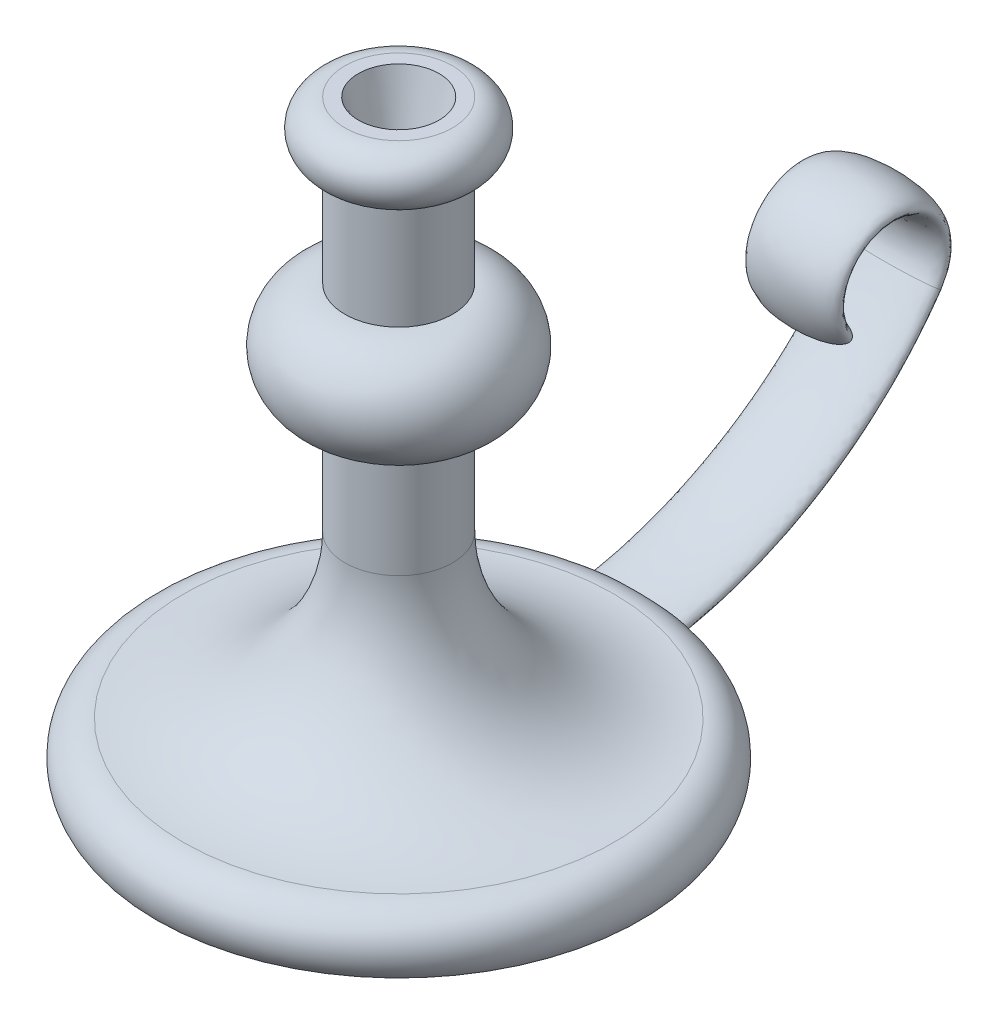
SolidWorks part; units mm, degrees
ref_plane "Спереди" through (0, 0, 0) normal (0, 0, 1) x (1, 0, 0)
ref_plane "Сверху" through (0, 0, 0) normal (0, 1, 0) x (1, 0, 0)
ref_plane "Справа" through (0, 0, 0) normal (1, 0, 0) x (0, 0, -1)
sketch "Эскиз1" plane through (0, 0, 0) normal (0, 0, 1) x (1, 0, 0)
  line L0 (90, 0) -> (0, 0)
  line L1 (0, 0) -> (0, 220)
  line L2 (0, 220) -> (20, 220)
  line L3 (20, 200) -> (20, 160)
  line L4 (20, 120) -> (20, 80)
  arc A0 (20, 220) -> (20, 200) centre (20, 210) cw
  arc A1 (20, 160) -> (20, 120) centre (20, 140) cw
  arc A2 (20, 80) -> (80, 20) centre (80, 80) ccw
  arc A3 (80, 20) -> (90, 0) centre (80, 7.5) cw
  point P14 (0, 0)
  point P15 (0, 0)
  dimension "D4" = 10
  dimension "D5" = 20
  dimension "D7" = 60
  dimension "D8" = 12.5
  dimension "D1" = 20
  dimension "D2" = 220
  dimension "D3" = 90
  dimension "D6" = 40
  dimension "D9" = 80
revolve "Повернуть1" add sketch "Эскиз1" angle 360 about L1
sketch "Эскиз2" plane through (0, 0, 0) normal (1, 0, 0) x (0, 0, -1)
  line L0 (0, 10) -> (60, 10)
  line L1 (0, 227.4356) -> (0, 175.1288) construction
  arc A0 (60, 10) -> (183.5921, 75) centre (60, 160) ccw
  arc A1 (183.5921, 75) -> (150.6342, 75) centre (167.1131, 86.3333) ccw
  point P8 (0, 0)
  dimension "D2" = 150
  dimension "D4" = 20
  dimension "D1" = 60
  dimension "D3" = 65
  dimension "D5" = 10
sketch "Эскиз4" plane through (0, 0, 0) normal (0, 0, 1) x (1, 0, 0)
  ellipse E0 centre (0, 10) end of major axis (-17.5, 10) minor radius 5
  dimension "D1" = 10
  dimension "D2" = 35
sweep "По траектории1" add profiles "Эскиз4" path "Эскиз2"
sketch "Эскиз8" plane through (0, 220, 0) normal (0, 1, 0) x (1, 0, 0)
  circle A0 centre (0, 0) radius 15
  dimension "D1" = 30
extrude "Вырез-Вытянуть1" cut sketch "Эскиз8" against normal blind 25 draft 15
